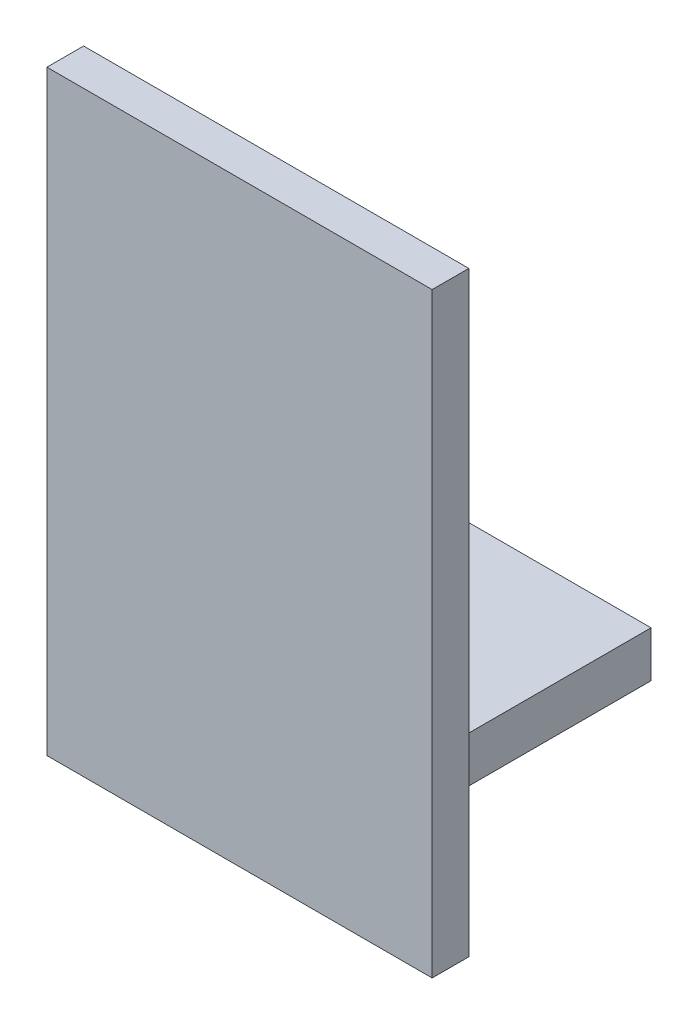
SolidWorks part; units mm, degrees
ref_plane "Спереди" through (0, 0, 0) normal (0, 0, 1) x (1, 0, 0)
ref_plane "Сверху" through (0, 0, 0) normal (0, 1, 0) x (1, 0, 0)
ref_plane "Справа" through (0, 0, 0) normal (1, 0, 0) x (0, 0, -1)
sketch "Эскиз1" plane through (0, 0, 0) normal (1, 0, 0) x (0, 0, -1)
  line L0 (0, 0) -> (0, 60)
  line L1 (0, 0) -> (36, 0)
  line L2 (36, 0) -> (36, -5)
  line L3 (36, -5) -> (-4, -5)
  line L4 (-4, -5) -> (-4, 60)
  line L5 (-4, 60) -> (0, 60)
extrude "Вытянуть1" add sketch "Эскиз1" against normal blind 42
sketch "Эскиз3" plane through (0, 0, 0) normal (0, 1, 0) x (1, 0, 0)
  line L0 (-16.1325, 36.3745) -> (-16.1325, 0)
  line L1 (-42, 0) -> (0, 0) construction
  line L2 (-16.1325, 0) -> (0, 0)
  line L3 (0, 0) -> (0, 36.3745)
  line L4 (0, -4) -> (0, 70) construction
  line L5 (0, 36.3745) -> (-16.1325, 36.3745)
extrude "Вырез-Вытянуть1" cut sketch "Эскиз3" against normal through all
